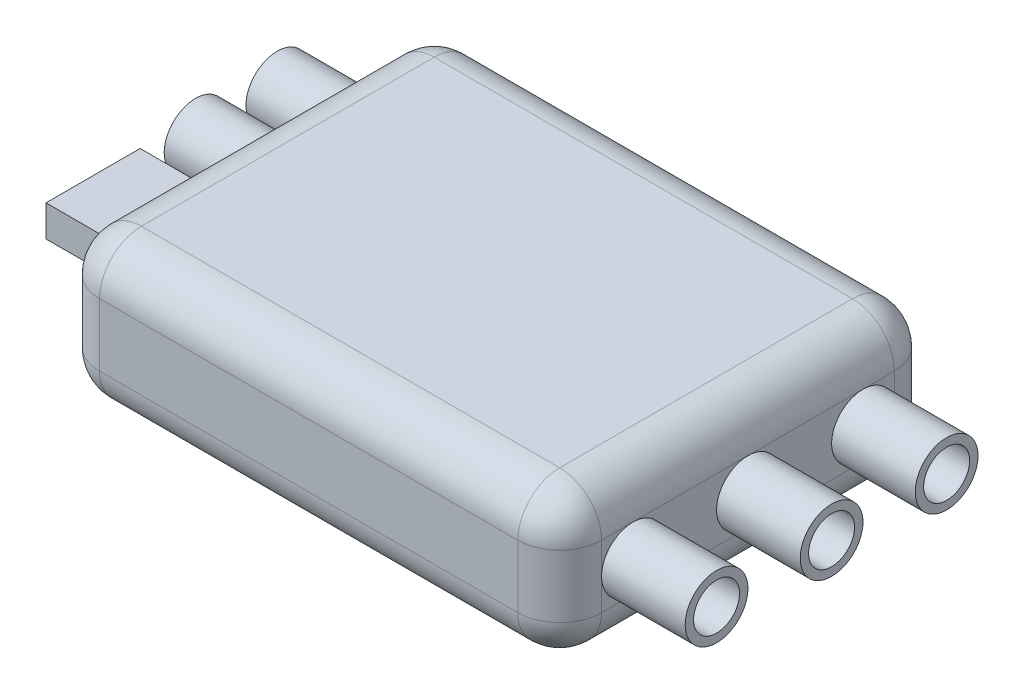
SolidWorks part; units mm, degrees
ref_plane "Front Plane" through (0, 0, 0) normal (0, 0, 1) x (1, 0, 0)
ref_plane "Top Plane" through (0, 0, 0) normal (0, 1, 0) x (1, 0, 0)
ref_plane "Right Plane" through (0, 0, 0) normal (1, 0, 0) x (0, 0, -1)
sketch "Sketch1" plane through (0, 0, 0) normal (0, 1, 0) x (1, 0, 0)
  line L1 (-10, 9) -> (10, 9)
  line L2 (-12, 7) -> (-12, -7)
  line L3 (-10, -9) -> (10, -9)
  line L4 (12, 7) -> (12, -7)
  line L5 (-12, 9) -> (12, -9) construction
  line L6 (-12, -9) -> (12, 9) construction
  arc A0 (10, 9) -> (12, 7) centre (10, 7) cw
  arc A1 (-12, -7) -> (-10, -9) centre (-10, -7) ccw
  arc A2 (-10, 9) -> (-12, 7) centre (-10, 7) ccw
  arc A3 (10, -9) -> (12, -7) centre (10, -7) ccw
  point P0 (0, 0)
  dimension "D3" = 2
  dimension "D1" = 24
  dimension "D2" = 18
extrude "Boss-Extrude1" add sketch "Sketch1" along normal blind 7
fillet "Fillet1" radius 2 16 edges at (0, 0, -9) (-11.4142, 0, -8.4142) (-12, 0, 0) (-11.4142, 0, 8.4142) (0, 0, 9) (11.4142, 0, 8.4142) (12, 0, 0) (11.4142, 0, -8.4142) (12, 7, 0) (11.4142, 7, 8.4142) (0, 7, 9) (-11.4142, 7, 8.4142) (-12, 7, 0) (-11.4142, 7, -8.4142) (0, 7, -9) (11.4142, 7, -8.4142)
sketch "Sketch2" plane through (12, 0, 0) normal (1, 0, 0) x (0, 0, -1)
  line L0 (-7, 5) -> (-7, 2) construction
  line L1 (7, 5) -> (7, 2) construction
  circle A0 centre (-5.5, 3.5) radius 1.5
  circle A1 centre (0, 3.5) radius 1.5
  circle A2 centre (5.5, 3.5) radius 1.5
  circle A3 centre (-5.5, 3.5) radius 1.1
  circle A4 centre (0, 3.5) radius 1.1
  circle A5 centre (5.5, 3.5) radius 1.1
  point P10 (7, 3.5)
  dimension "D1" = 3
  dimension "D2" = 0.4
extrude "Boss-Extrude2" add sketch "Sketch2" along normal blind 4
sketch "Sketch3" plane through (-12, 0, 0) normal (-1, 0, 0) x (0, 0, 1)
  line L0 (-7, 5) -> (-7, 2) construction
  line L1 (1.06, 4.25) -> (5.56, 4.25)
  line L2 (1.06, 4.25) -> (1.06, 2.75)
  line L3 (1.06, 2.75) -> (5.56, 2.75)
  line L4 (5.56, 4.25) -> (5.56, 2.75)
  line L5 (1.06, 4.25) -> (5.56, 2.75) construction
  line L6 (1.06, 2.75) -> (5.56, 4.25) construction
  circle A0 centre (-5.5, 3.5) radius 1.5
  circle A1 centre (-1.59, 3.5) radius 1.5
  circle A2 centre (-5.5, 3.5) radius 1.1
  circle A3 centre (-1.59, 3.5) radius 1.1
  point P4 (3.31, 3.5)
  point P11 (-7, 3.5)
  point P12 (0, 0)
  dimension "D1" = 3
  dimension "D2" = 3.91
  dimension "D3" = 4.5
  dimension "D4" = 4.9
  dimension "D5" = 1.5
  dimension "D6" = 0.4
extrude "Boss-Extrude3" add sketch "Sketch3" along normal blind 4
